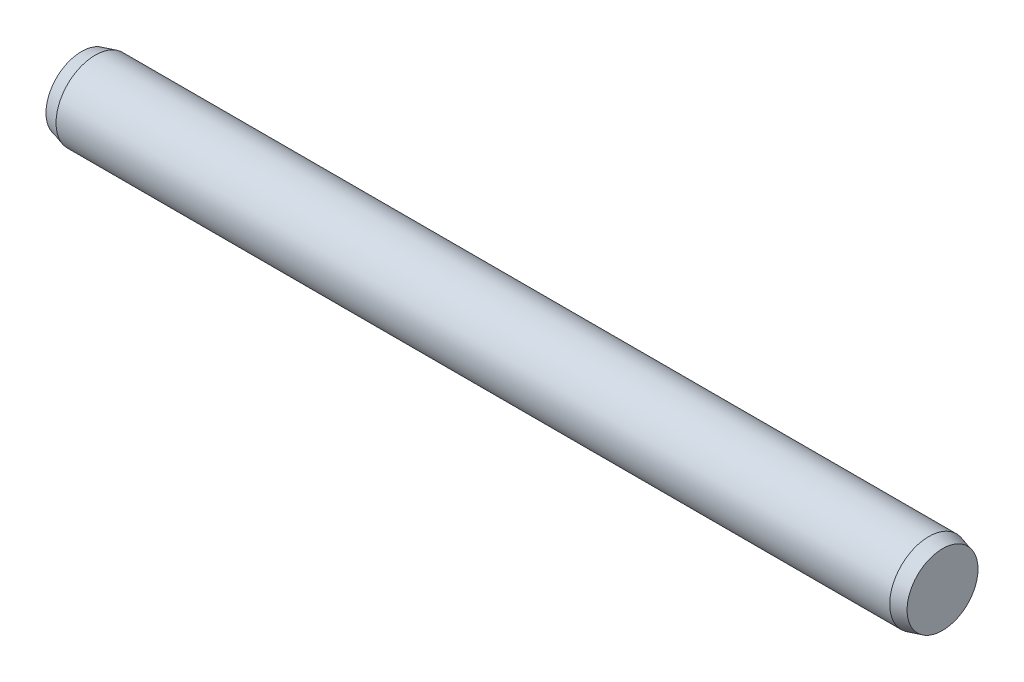
SolidWorks part; units mm, degrees
ref_plane "Front Plane" through (0, 0, 0) normal (0, 0, 1) x (1, 0, 0)
ref_plane "Top Plane" through (0, 0, 0) normal (0, 1, 0) x (1, 0, 0)
ref_plane "Right Plane" through (0, 0, 0) normal (1, 0, 0) x (0, 0, -1)
sketch "Sketch1" plane through (0, 0, 0) normal (0, 0, 1) x (1, 0, 0)
  line L0 (-10.65, 0) -> (10.65, 0) construction
  line L1 (10.65, 1) -> (10.65, -1) construction
  line L2 (-10.65, 1) -> (-10.65, -1) construction
  line L3 (11, 1) -> (11, -1) construction
  line L4 (-11, 1) -> (-11, -1) construction
  line L5 (-10.65, 0) -> (-11, 0) construction
  line L6 (10.65, 0) -> (11, 0) construction
  dimension "D1" = 0.35
  dimension "Dia" = 2
  dimension "Length" = 22
  dimension "C" = 0.35
sketch "Sketch2" plane through (0, 0, 0) normal (1, 0, 0) x (0, 0, -1)
  circle A0 centre (0, 0) radius 1
extrude "Extrude1" add sketch "Sketch2" against normal up to vertex (10.65 mm away) and the other way up to vertex (10.65 mm away) up to point (-10.65, 1, 0) other way up to point (10.65, 1, 0)
sketch "Sketch3" plane through (10.65, 0, 0) normal (1, 0, 0) x (0, 0, -1)
  circle A1 centre (0, 0) radius 1
  circle A2 centre (0, 0) radius 1
  dimension "D1" = 0
extrude "Extrude2" add sketch "Sketch3" along normal up to vertex (0.35 mm away) draft 15 up to point (11, 0, 0)
sketch "Sketch4" plane through (-10.65, 0, 0) normal (-1, 0, 0) x (0, 0, 1)
  circle A1 centre (0, 0) radius 1
  circle A2 centre (0, 0) radius 1
  dimension "D1" = 0
extrude "Extrude3" add sketch "Sketch4" along normal up to vertex (0.35 mm away) draft 15 up to point (-11, 0, 0)
equation "\"D1@Sketch1\" = \"C@Sketch1\""
